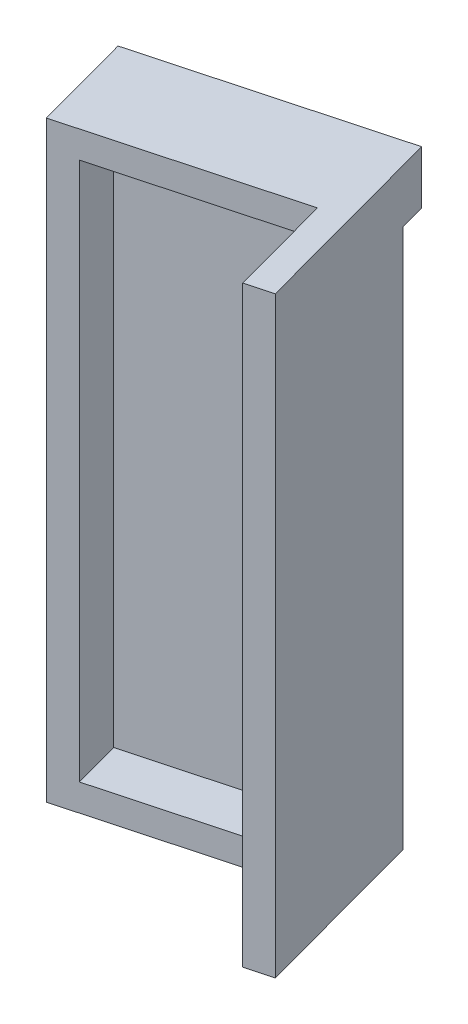
SolidWorks part; units mm, degrees
ref_plane "Alzado" through (0, 0, 0) normal (0, 0, 1) x (1, 0, 0)
ref_plane "Planta" through (0, 0, 0) normal (0, 1, 0) x (1, 0, 0)
ref_plane "Vista lateral" through (0, 0, 0) normal (1, 0, 0) x (0, 0, -1)
sketch "Croquis1" plane through (0, 0, 0) normal (0, 0, 1) x (1, 0, 0)
  line L1 (-65.2968, 25.2877) -> (-13.2968, 25.2877)
  line L2 (-65.2968, 25.2877) -> (-65.2968, -11.7123)
  line L3 (-65.2968, -11.7123) -> (-13.2968, -11.7123)
  line L4 (-13.2968, 25.2877) -> (-13.2968, -11.7123)
  dimension "D1" = 52
  dimension "D2" = 37
extrude "Saliente-Extruir1" add sketch "Croquis1" along normal blind 3
fillet "Redondeo1" radius 3 2 edges at (-65.2968, -11.7123, 1.5) (-65.2968, 25.2877, 1.5)
sketch "Croquis2" plane through (0, 0, 3) normal (0, 0, 1) x (1, 0, 0)
  line L0 (-62.2968, -11.7123) -> (-13.2968, -11.7123) construction
  line L3 (-65.2968, 22.2877) -> (-65.2968, -8.7123) construction
  circle A0 centre (-61.2968, 21.2877) radius 1.5
  circle A1 centre (-61.2968, -7.7123) radius 1.5
  circle A2 centre (-16.6241, -7.7123) radius 1.5
  circle A3 centre (-17.2968, 21.2877) radius 1.5
  dimension "D1" = 29
  dimension "D4" = 29
  dimension "D2" = 4
  dimension "D3" = 4
  dimension "D5" = 44
  dimension "D6" = 4
extrude "Cortar-Extruir1" cut sketch "Croquis2" against normal blind 3
sketch "Croquis3" plane through (0, 0, 3) normal (0, 0, 1) x (1, 0, 0)
  line L0 (-65.2968, 22.2877) -> (-65.2968, -8.7123) construction
  line L1 (-65.2968, 16.7877) -> (-36.2968, 16.7877)
  line L2 (-65.2968, 16.7877) -> (-65.2968, -3.2123)
  line L3 (-65.2968, -3.2123) -> (-36.2968, -3.2123)
  line L4 (-36.2968, 16.7877) -> (-36.2968, -3.2123)
  line L5 (-62.2968, -11.7123) -> (-13.2968, -11.7123) construction
  line L7 (-13.2968, -11.7123) -> (-13.2968, 25.2877) construction
  line L9 (-13.2968, 13.7877) -> (-19.2968, 13.7877)
  line L10 (-13.2968, 13.7877) -> (-13.2968, -0.2123)
  line L11 (-13.2968, -0.2123) -> (-19.2968, -0.2123)
  line L12 (-19.2968, 13.7877) -> (-19.2968, -0.2123)
  dimension "D1" = 29
  dimension "D2" = 20
  dimension "D3" = 8.5
  dimension "D4" = 6
  dimension "D5" = 14
  dimension "D6" = 11.5
extrude "Cortar-Extruir2" cut sketch "Croquis3" against normal blind 3
sketch "Croquis4" plane through (0, 0, 3) normal (0, 0, 1) x (1, 0, 0)
  line L0 (-57.2968, 16.7877) -> (-57.2968, 20.7902)
  line L1 (-36.2968, 16.7877) -> (-65.2968, 16.7877) construction
  line L2 (-57.2968, 20.7902) -> (-26.2968, 20.7902)
  line L3 (-26.2968, 20.7902) -> (-26.2968, -7.2123)
  line L4 (-26.2968, -7.2123) -> (-57.2968, -7.2123)
  line L5 (-57.2968, -7.2123) -> (-57.2968, -3.2123)
  line L6 (-65.2968, -3.2123) -> (-36.2968, -3.2123) construction
  line L7 (-57.2968, -3.2123) -> (-36.2968, -3.2123)
  line L8 (-36.2968, -3.2123) -> (-36.2968, 16.7877)
  line L9 (-36.2968, 16.7877) -> (-57.2968, 16.7877)
  line L10 (-65.2968, 22.2877) -> (-65.2968, 16.7877) construction
  line L11 (-65.2968, -3.2123) -> (-65.2968, -8.7123) construction
  dimension "D1" = 4
  dimension "D2" = 10
  dimension "D3" = 4.0026
  dimension "D4" = 8
  dimension "D5" = 8
extrude "Saliente-Extruir2" add sketch "Croquis4" along normal blind 9
sketch "Croquis5" plane through (0, 0, 12) normal (0, 0, 1) x (1, 0, 0)
  line L1 (-26.2968, 20.7902) -> (-62.2968, 20.7902)
  line L2 (-26.2968, 20.7902) -> (-26.2968, -7.2123)
  line L3 (-26.2968, -7.2123) -> (-62.2968, -7.2123)
  line L4 (-62.2968, 20.7902) -> (-62.2968, -7.2123)
  dimension "D1" = 28.0026
  dimension "D2" = 36
extrude "Saliente-Extruir3" add sketch "Croquis5" along normal blind 10.3
sketch "Croquis6" plane through (0, -7.2123, 0) normal (0, -1, 0) x (1, 0, 0)
  line L0 (-35.2968, 15) -> (-35.2968, 12.9954)
  line L2 (-35.2968, 12.9954) -> (-26.2968, 12.9954)
  line L3 (-35.2968, 15) -> (-62.2968, 22.3)
  line L6 (-26.2968, 22.3) -> (-26.2968, 3) construction
  line L7 (-26.2968, 14.7574) -> (-26.2968, 22.3)
  line L8 (-26.2968, 22.3) -> (-62.2968, 22.3)
  line L9 (-26.2968, 12.9954) -> (-26.2968, 14.7574)
extrude "Cortar-Extruir3" cut sketch "Croquis6" against normal up to vertex
sketch "Croquis7" plane through (1.3749, 0, 5.0851) normal (0.261, 0, 0.9653) x (0.9653, 0, -0.261)
  line L0 (-65.9578, 6.7889) -> (-65.9578, -26.7111)
  line L1 (-65.9578, 20.7902) -> (-65.9578, -7.2123) construction
  line L2 (-65.9578, -26.7111) -> (-37.9578, -26.7111)
  line L3 (-37.9578, -26.7111) -> (-37.9578, 40.2889)
  line L4 (-37.9578, 40.2889) -> (-65.9578, 40.2889)
  line L5 (-65.9578, 40.2889) -> (-65.9578, 6.7889)
  dimension "D1" = 28
  dimension "D2" = 67
  dimension "D3" = 33.5
  dimension "D4" = 33.5
extrude "Saliente-Extruir4" add sketch "Croquis7" along normal blind 8.5
sketch "Croquis8" plane through (3.5933, 0, 13.2905) normal (0.261, 0, 0.9653) x (0.9653, 0, -0.261)
  line L0 (-65.9578, -26.7111) -> (-37.9578, -26.7111) construction
  line L1 (-62.9078, -23.6611) -> (-41.0078, -23.6611)
  line L2 (-62.9078, -23.6611) -> (-62.9078, 37.2389)
  line L3 (-62.9078, 37.2389) -> (-41.0078, 37.2389)
  line L4 (-41.0078, -23.6611) -> (-41.0078, 37.2389)
  line L5 (-37.9578, 40.2889) -> (-65.9578, 40.2889) construction
  line L6 (-65.9578, 40.2889) -> (-65.9578, -26.7111) construction
  line L7 (-37.9578, -26.7111) -> (-37.9578, 40.2889) construction
  dimension "D1" = 3.05
  dimension "D2" = 3.05
  dimension "D3" = 3.05
  dimension "D4" = 3.05
extrude "Cortar-Extruir4" cut sketch "Croquis8" against normal blind 5.5
sketch "Croquis10" plane through (0, 20.7902, 0) normal (0, 1, 0) x (1, 0, 0)
  line L0 (-62.2968, -22.3) -> (-35.2968, -15)
  line L1 (-35.2968, -15) -> (-35.2968, -12)
  line L2 (-35.2968, -12) -> (-62.2968, -19.3)
  line L3 (-62.2968, -22.3) -> (-62.2968, -12) construction
  line L4 (-62.2968, -19.3) -> (-62.2968, -22.3)
extrude "Cortar-Extruir5" cut sketch "Croquis10" against normal blind 9
sketch "Croquis12" plane through (0, 20.7902, 0) normal (0, 1, 0) x (1, 0, 0)
  line L0 (-26.2968, -12.9954) -> (-35.2968, -12.9954)
  line L1 (-26.2968, -12.9954) -> (-26.2968, -11.4245)
  line L2 (-26.2968, -12.9954) -> (-26.2968, -3) construction
  line L4 (-26.2968, -11.4245) -> (-35.2968, -11.4245)
  line L5 (-35.2968, -11.4245) -> (-35.2968, -12.9954)
extrude "Cortar-Extruir6" cut sketch "Croquis12" against normal up to vertex
sketch "Croquis13" plane through (3.5933, 0, 13.2905) normal (0.261, 0, 0.9653) x (0.9653, 0, -0.261)
  line L0 (-37.9578, 40.2889) -> (-65.9578, 40.2889) construction
  line L1 (-37.9578, -26.7111) -> (-40.9578, -26.7111)
  line L2 (-37.9578, -26.7111) -> (-37.9578, 40.2889)
  line L3 (-37.9578, 40.2889) -> (-40.9578, 40.2889)
  line L4 (-40.9578, -26.7111) -> (-40.9578, 40.2889)
extrude "Saliente-Extruir5" add sketch "Croquis13" along normal blind 12
sketch "Croquis14" plane through (0, -7.2123, 0) normal (0, -1, 0) x (1, 0, 0)
  line L1 (-57.2968, 12) -> (-26.2968, 12)
  line L2 (-57.2968, 12) -> (-57.2968, 3)
  line L3 (-57.2968, 3) -> (-26.2968, 3)
  line L4 (-26.2968, 12) -> (-26.2968, 3)
extrude "Cortar-Extruir7" cut sketch "Croquis14" against normal up to vertex
sketch "Croquis17" plane through (0, 0, 3) normal (0, 0, 1) x (1, 0, 0)
  line L0 (-13.2968, -0.2123) -> (-19.2968, -0.2123)
  line L1 (-19.2968, -0.2123) -> (-19.2968, 13.7877)
  line L2 (-19.2968, 13.7877) -> (-13.2968, 13.7877)
  line L3 (-13.2968, 13.7877) -> (-13.2968, 25.2877)
  line L4 (-13.2968, 25.2877) -> (-62.2968, 25.2877)
  line L5 (-65.2968, 22.2877) -> (-65.2968, 16.7877)
  line L7 (-65.2968, 16.7877) -> (-36.2968, 16.7877)
  line L8 (-36.2968, 16.7877) -> (-36.2968, -3.2123)
  line L9 (-36.2968, -3.2123) -> (-65.2968, -3.2123)
  line L10 (-65.2968, -3.2123) -> (-65.2968, -8.7123)
  line L11 (-62.2968, -11.7123) -> (-13.2968, -11.7123)
  line L12 (-13.2968, -11.7123) -> (-13.2968, -0.2123)
  arc A0 (-62.2968, -11.7123) -> (-65.2968, -8.7123) centre (-62.2968, -8.7123) cw
  arc A1 (-65.2968, 22.2877) -> (-62.2968, 25.2877) centre (-62.2968, 22.2877) cw
  circle A2 centre (-61.2968, 21.2877) radius 1.5
  circle A3 centre (-61.2968, -7.7123) radius 1.5
  circle A4 centre (-16.6241, -7.7123) radius 1.5
  circle A5 centre (-17.2968, 21.2877) radius 1.5
extrude "Saliente-Extruir6" add sketch "Croquis17" along normal up to vertex (9 mm away)
sketch "Croquis18" plane through (0, -11.7123, 0) normal (0, -1, 0) x (1, 0, 0)
  line L1 (-13.2968, 0) -> (-67.494, 0)
  line L2 (-13.2968, 0) -> (-13.2968, 9)
  line L3 (-13.2968, 9) -> (-67.494, 9)
  line L4 (-67.494, 0) -> (-67.494, 9)
  dimension "D1" = 9
extrude "Cortar-Extruir8" cut sketch "Croquis18" against normal up to vertex
sketch "Croquis20" plane through (1.3749, 0, 5.0851) normal (-0.261, 0, -0.9653) x (-0.9653, 0, 0.261)
  line L0 (37.9578, -26.7111) -> (37.9578, 40.2889) construction
  line L1 (65.9578, 40.2889) -> (37.9578, 40.2889)
  line L2 (65.9578, 40.2889) -> (65.9578, 34.2889)
  line L3 (65.9578, 34.2889) -> (37.9578, 34.2889)
  line L4 (37.9578, 40.2889) -> (37.9578, 34.2889)
  dimension "D1" = 6
extrude "Saliente-Extruir7" add sketch "Croquis20" along normal blind 3
sketch "Croquis21" plane through (0, 0, 9) normal (0, 0, -1) x (-1, 0, 0)
  line L0 (65.2968, 16.7877) -> (36.2968, 16.7877) construction
  line L1 (55.2968, 16.7877) -> (35.2968, 16.7877)
  line L2 (55.2968, 16.7877) -> (55.2968, 21.2877)
  line L3 (55.2968, 21.2877) -> (35.2968, 21.2877)
  line L4 (35.2968, 16.7877) -> (35.2968, 21.2877)
  line L5 (36.2968, -3.2123) -> (65.2968, -3.2123) construction
  line L6 (55.2968, -3.2123) -> (35.2968, -3.2123)
  line L7 (55.2968, -3.2123) -> (55.2968, -7.7123)
  line L8 (55.2968, -7.7123) -> (35.2968, -7.7123)
  line L9 (35.2968, -3.2123) -> (35.2968, -7.7123)
  line L10 (13.2968, 25.2877) -> (62.2968, 25.2877) construction
  line L11 (13.2968, -11.7123) -> (62.2968, -11.7123) construction
  line L12 (65.2968, 22.2877) -> (65.2968, 16.7877) construction
  line L13 (65.2968, -3.2123) -> (65.2968, -8.7123) construction
  dimension "D1" = 4
  dimension "D2" = 4
  dimension "D3" = 10
  dimension "D4" = 10
  dimension "D5" = 20
  dimension "D6" = 20
extrude "Cortar-Extruir10" cut sketch "Croquis21" against normal blind 2
sketch "Croquis24" plane through (3.5933, 0, 13.2905) normal (0.261, 0, 0.9653) x (0.9653, 0, -0.261)
  line L0 (-40.9578, 40.2889) -> (-40.9578, -26.7111) construction
  line L1 (-41.0078, 37.2389) -> (-40.9578, 37.2389)
  line L2 (-41.0078, 37.2389) -> (-41.0078, -23.6611)
  line L3 (-41.0078, -23.6611) -> (-40.9578, -23.6611)
  line L4 (-40.9578, 37.2389) -> (-40.9578, -23.6611)
extrude "Cortar-Extruir13" cut sketch "Croquis24" against normal up to vertex (5.5 mm away)
sketch "Croquis25" plane through (1.3749, 0, 5.0851) normal (-0.261, 0, -0.9653) x (-0.9653, 0, 0.261)
  line L1 (77.4118, 34.2889) -> (13.183, 34.2889)
  line L2 (77.4118, 34.2889) -> (77.4118, -26.7111)
  line L3 (77.4118, -26.7111) -> (13.183, -26.7111)
  line L4 (13.183, 34.2889) -> (13.183, -26.7111)
extrude "Cortar-Extruir14" cut sketch "Croquis25" along normal blind 15
sketch "Croquis26" plane through (0, 0, 12) normal (0, 0, 1) x (1, 0, 0)
  line L1 (-24.2009, 25.2877) -> (-13.2968, 25.2877)
  line L2 (-24.2009, 25.2877) -> (-24.2009, -11.7123)
  line L3 (-24.2009, -11.7123) -> (-13.2968, -11.7123)
  line L4 (-13.2968, 25.2877) -> (-13.2968, -11.7123)
extrude "Cortar-Extruir15" cut sketch "Croquis26" against normal blind 15
